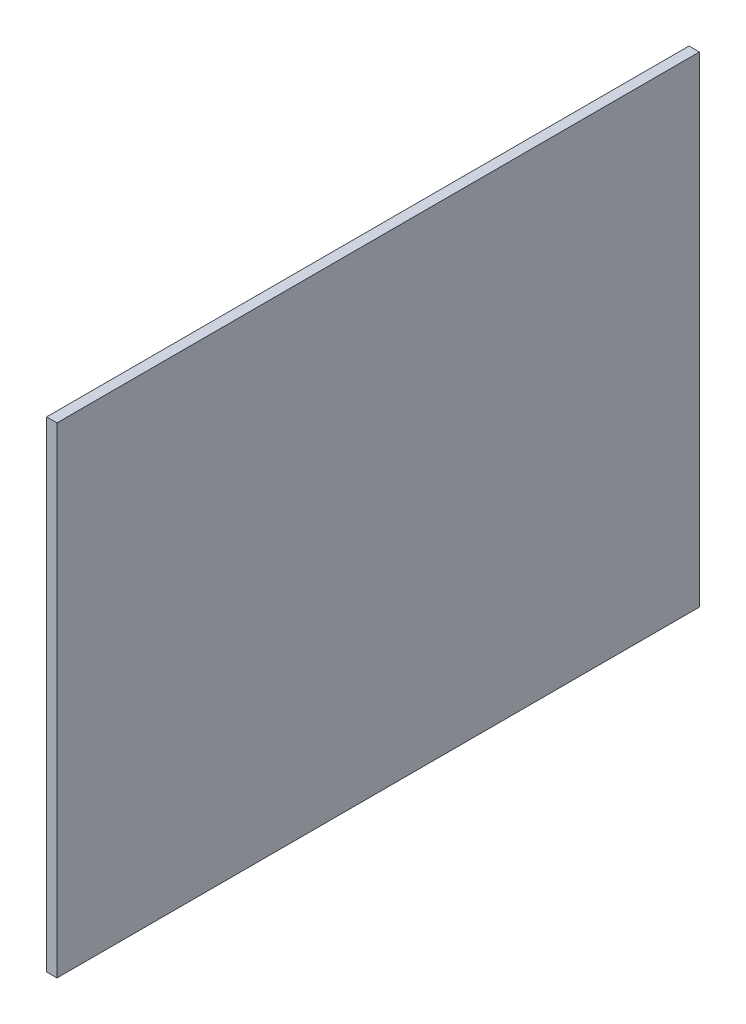
SolidWorks part; units mm, degrees
ref_plane "Front" through (0, 0, 0) normal (0, 0, 1) x (1, 0, 0)
ref_plane "Top" through (0, 0, 0) normal (0, 1, 0) x (1, 0, 0)
ref_plane "Right" through (0, 0, 0) normal (1, 0, 0) x (0, 0, -1)
sketch "Sketch1" plane through (0, 0, 0) normal (0, 0, 1) x (1, 0, 0)
  line L0 (0, 0) -> (0, 73.66)
  line L1 (0, 73.66) -> (1.5875, 73.66)
  line L2 (1.5875, 73.66) -> (1.5875, 0)
  line L3 (1.5875, 0) -> (0, 0)
  dimension "D1" = 1.5875
  dimension "D2" = 73.66
extrude "Boss-Extrude1" add sketch "Sketch1" along normal blind 98.425
